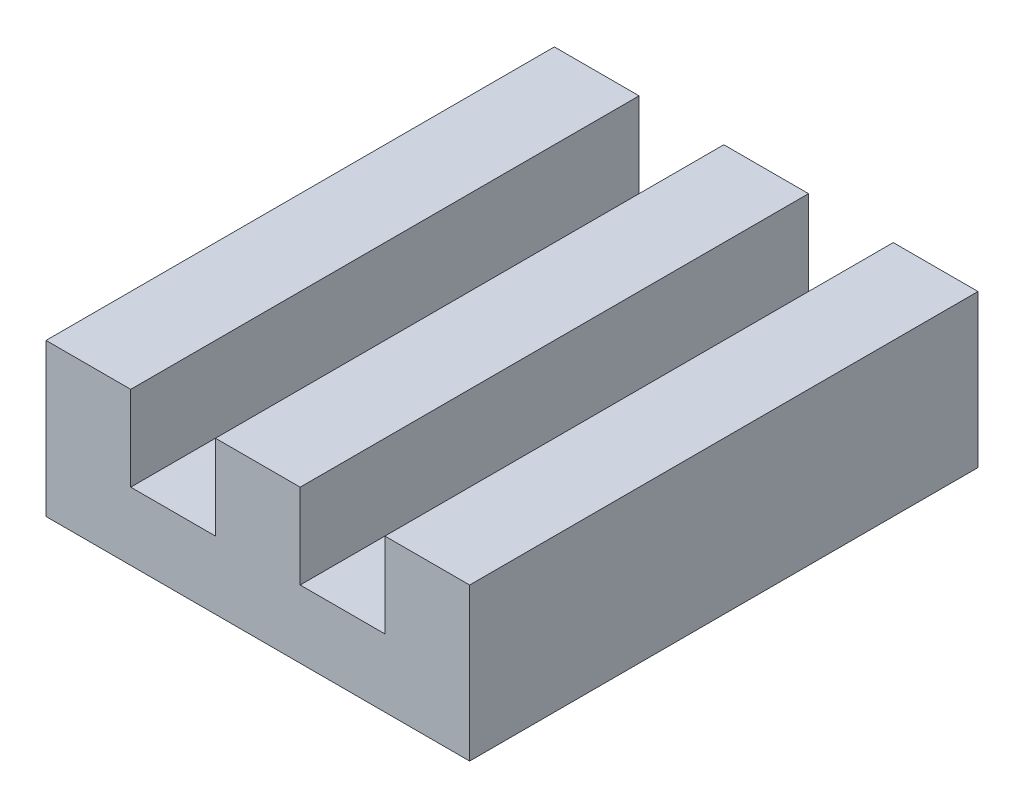
SolidWorks part; units mm, degrees
ref_plane "Plan de face" through (0, 0, 0) normal (0, 0, 1) x (1, 0, 0)
ref_plane "Plan de dessus" through (0, 0, 0) normal (0, 1, 0) x (1, 0, 0)
ref_plane "Plan de droite" through (0, 0, 0) normal (1, 0, 0) x (0, 0, -1)
sketch "Esquisse1" plane through (0, 0, 0) normal (0, 0, 1) x (1, 0, 0)
  line L0 (0, 0) -> (50, 0)
  line L1 (50, 0) -> (50, 9)
  line L3 (50, 9) -> (50, 18)
  line L4 (50, 18) -> (0, 18)
  line L5 (0, 18) -> (0, 0)
  dimension "D1" = 50
  dimension "D2" = 18
  dimension "D3" = 9
extrude "Boss.-Extru.1" add sketch "Esquisse1" along normal blind 60
sketch "Esquisse2" plane through (0, 18, 0) normal (0, 1, 0) x (1, 0, 0)
  line L0 (0, -60) -> (0, 0) construction
  line L1 (10, 4.9465) -> (20, 4.9465)
  line L2 (10, 4.9465) -> (10, -65.2969)
  line L3 (10, -65.2969) -> (20, -65.2969)
  line L4 (20, 4.9465) -> (20, -65.2969)
  line L5 (30, 4.9465) -> (40, 4.9465)
  line L6 (30, 4.9465) -> (30, -65.2969)
  line L7 (30, -65.2969) -> (40, -65.2969)
  line L8 (40, 4.9465) -> (40, -65.2969)
  line L9 (50, -60) -> (50, 0) construction
  dimension "D1" = 10
  dimension "D2" = 10
  dimension "D3" = 10
  dimension "D4" = 10
extrude "Enlèv. mat.-Extru.1" cut sketch "Esquisse2" against normal blind 10
